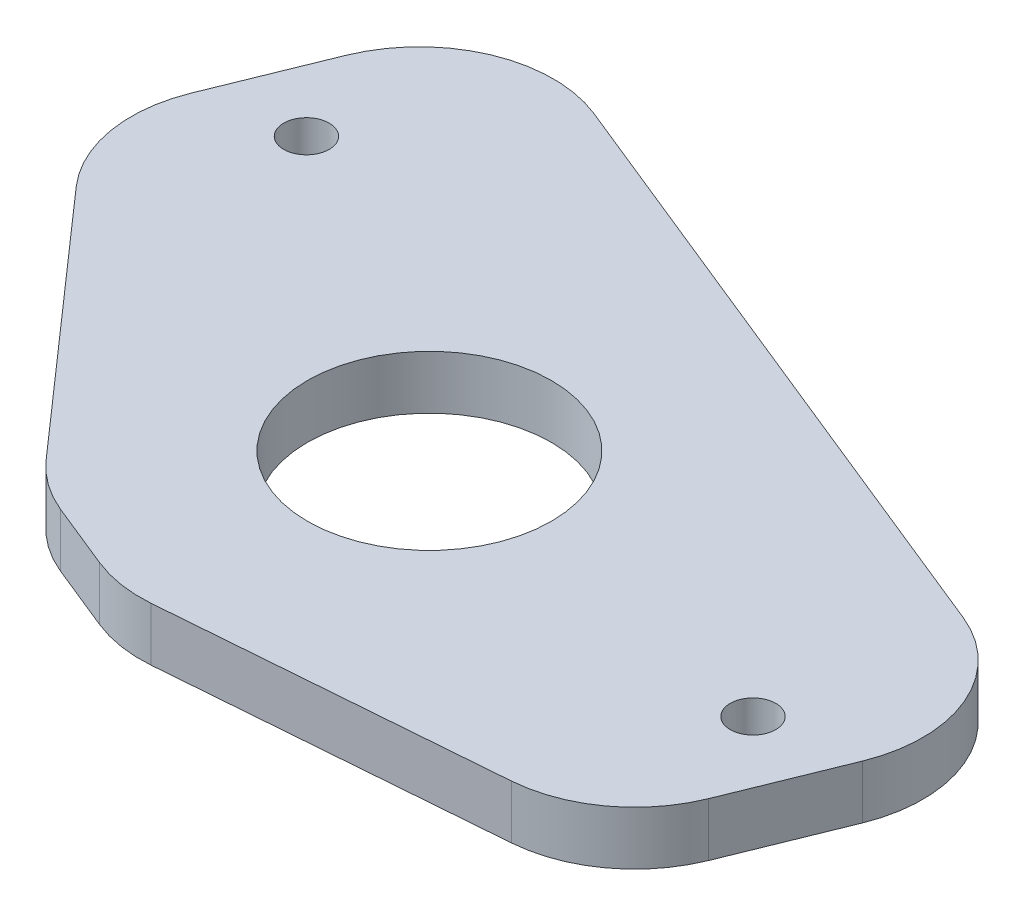
SolidWorks part; units mm, degrees
ref_plane "前视基准面" through (0, 0, 0) normal (0, 0, 1) x (1, 0, 0)
ref_plane "上视基准面" through (0, 0, 0) normal (0, 1, 0) x (1, 0, 0)
ref_plane "右视基准面" through (0, 0, 0) normal (1, 0, 0) x (0, 0, -1)
sketch "草图1" plane through (0, 0, 0) normal (0, 1, 0) x (1, 0, 0)
  line L0 (-126.2404, 38.1285) -> (-191.1106, 64.4316)
  line L1 (-191.1106, 64.4316) -> (-206.141, 27.3629)
  line L2 (-206.141, 27.3629) -> (-141.2708, 1.0598)
  line L3 (-141.2708, 1.0598) -> (-126.2404, 38.1285)
  circle A0 centre (-136.9617, 27.6547) radius 1.7
  circle A1 centre (-191.1028, 48.4832) radius 1.7
  circle A2 centre (-166.1907, 32.7457) radius 9.1
  circle A3 centre (-166.1907, 32.7457) radius 12 construction
extrude "凸台-拉伸1" add sketch "草图1" along normal blind 4
sketch "草图2" plane through (0, 4, 0) normal (0, 1, 0) x (1, 0, 0)
  line L0 (-135.6344, 14.9606) -> (-169.0723, 12.3326)
  line L1 (-141.2708, 1.0598) -> (-126.2404, 38.1285) construction
  line L2 (-206.141, 27.3629) -> (-141.2708, 1.0598) construction
  line L3 (-169.0723, 12.3326) -> (-141.2708, 1.0598)
  line L4 (-141.2708, 1.0598) -> (-135.6344, 14.9606)
  line L5 (-200.5046, 41.2637) -> (-178.3395, 16.0902)
  line L6 (-191.1106, 64.4316) -> (-206.141, 27.3629) construction
  line L7 (-178.3395, 16.0902) -> (-206.141, 27.3629)
  line L8 (-206.141, 27.3629) -> (-200.5046, 41.2637)
  dimension "D1" = 15
  dimension "D2" = 30
  dimension "D3" = 30
  dimension "D4" = 15
extrude "切除-拉伸1" cut sketch "草图2" against normal blind 4
fillet "圆角1" radius 10 6 edges at (-126.2404, 2, -38.1285) (-191.1106, 2, -64.4316) (-200.5046, 2, -41.2637) (-178.3395, 2, -16.0902) (-169.0723, 2, -12.3326) (-135.6344, 2, -14.9606)
